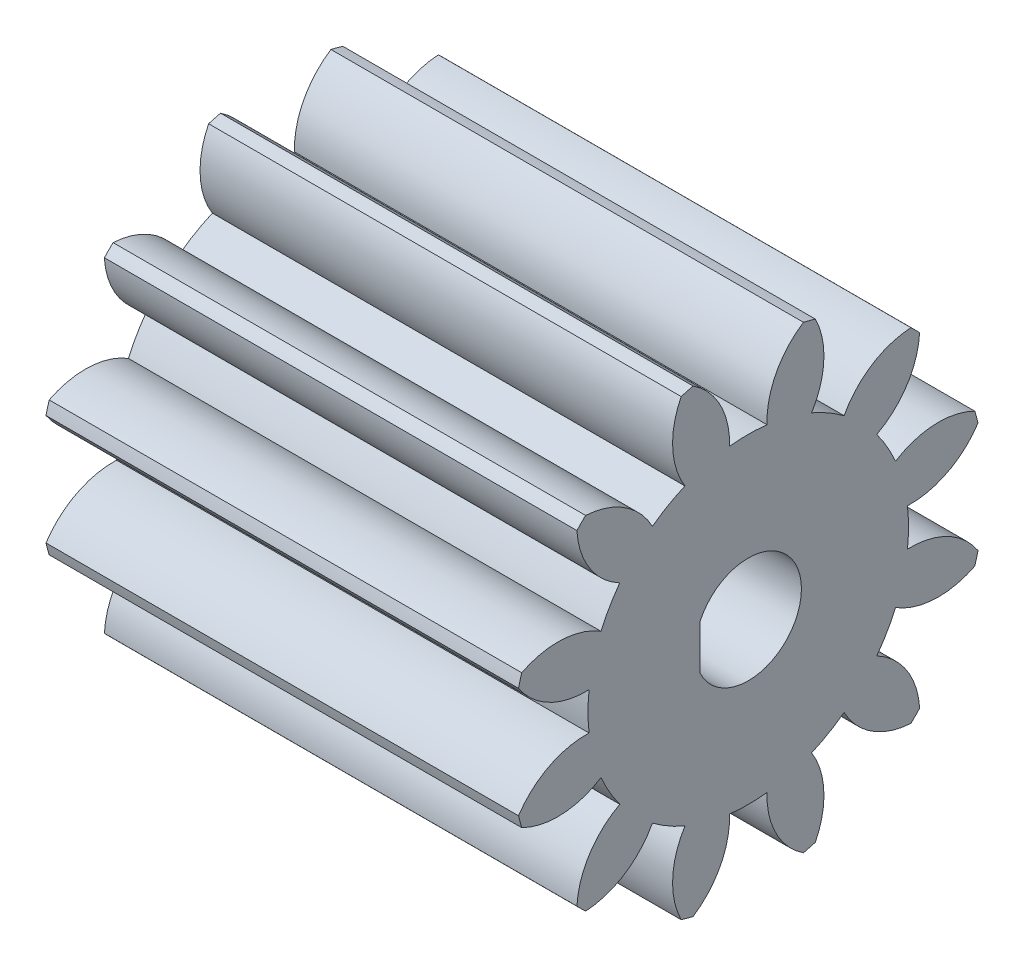
SolidWorks part; units mm, degrees
ref_plane "Plane1" through (0, 0, 0) normal (0, 0, 1) x (1, 0, 0)
ref_plane "Plane2" through (0, 0, 0) normal (0, 1, 0) x (1, 0, 0)
ref_plane "Plane3" through (0, 0, 0) normal (1, 0, 0) x (0, 0, -1)
sketch "HoldingSke" plane through (0, 0, 0) normal (0, 1, 0) x (1, 0, 0)
  line L0 (0, 0) -> (0.4891, -0.104)
  line L1 (-15, 0) -> (100, 0) construction
  line L2 (0, 0) -> (-2.1039, 2.3779)
  line L3 (0, 0) -> (-11.863, 4.5341)
  line L4 (0, 0) -> (8.4473, 1.7955)
  line L5 (0, 0) -> (-46.8476, -17.4728)
  line L6 (0, 0) -> (-23.211, -15.6605)
  line L7 (-2.1039, 2.3779) -> (8.6586, 51.2059)
  line L8 (-76.2, 54.61) -> (-74.4, 54.61)
  line L9 (-71.009, 38.7566) -> (-53.1078, 45.2721)
  line L10 (-76.2, 71.12) -> (104.1128, 71.12)
  line L11 (0, 0) -> (-28, 0)
  line L12 (-76.2, 101.6) -> (-76.133, 101.6)
  line L13 (24.9733, 27.94) -> (52.9518, 28.4284)
  line L14 (24.9733, 27.94) -> (24.9743, 27.94)
  line L15 (24.9733, 27.94) -> (100.4006, 29.5858)
  line L16 (-63.627, -2) -> (-12.827, -2)
  circle A0 centre (0, 0) radius 5
  circle A1 centre (0, 0) radius 9.499
  circle A2 centre (0, 0) radius 37.5
  circle A3 centre (0, 0) radius 5
  dimension "MHD" = 18.998
  dimension "Hub_dia" = 75
  dimension "Bore" = 10
  dimension "MBD" = 10
  dimension "Num_teeth" = 12
  dimension "Pitch" = 0.5
  dimension "Overall_len" = 50
  dimension "Show_teeth" = 12
  dimension "Thickness" = 28
  dimension "OAL" = 50.0001
  dimension "T_dim" = 1.8
  dimension "Ap" = 20
  dimension "H" = 19.05
  dimension "Pitch_radius" = 180.3128
  dimension "Width" = 28
  dimension "Backlash" = 0.067
  dimension "Addendum_fac" = 1
  dimension "Dedendum_fac" = 1.25
  dimension "Clearance_fac" = 0.25
  dimension "Dedendum_add" = 0.001
  dimension "Module" = 2
sketch "BasProSke" plane through (0, 0, 0) normal (0, 1, 0) x (1, 0, 0)
  line L0 (-10, 0) -> (60, 0) construction
  line L1 (0, 0) -> (0, 14)
  line L2 (0, 0) -> (28, 0)
  line L3 (28, 0) -> (28, 14)
  line L4 (28, 14) -> (0, 14)
  dimension "Thickness" = 28
  dimension "Diameter" = 28
revolve "Base-Revolve" add sketch "BasProSke" angle 360 about L0
sketch "TooCutSke" plane through (0, 0, 0) normal (1, 0, 0) x (0, 0, -1)
  line L1 (0, 0) -> (0, 107) construction
  line L2 (0, 0) -> (-1.6834, 11.8813) construction
  line L3 (0, 0) -> (-6.1662, 23.0126) construction
  line L4 (-1.6834, 11.8813) -> (-3.0831, 11.5063) construction
  arc A0 (1.1119, 9.4337) -> (-1.1119, 9.4337) centre (0, 0) ccw
  arc A1 (3.2981, 13.6321) -> (-3.2981, 13.6321) centre (0, 0) ccw
  circle A2 centre (0, 0) radius 12 construction
  circle A3 centre (0, 0) radius 11.2763 construction
  arc A4 (-1.1119, 9.4337) -> (-3.2981, 13.6321) centre (-5.9089, 9.6042) ccw
  arc A5 (3.2981, 13.6321) -> (1.1119, 9.4337) centre (5.9089, 9.6042) ccw
  dimension "Root_dia" = 18.998
  dimension "Overcut_dia" = 28.0508
  dimension "Pitch_dia" = 24
  dimension "Base_dia" = 22.5526
  dimension "Flank_rad" = 4.8
  dimension "Half_ang" = 15
  dimension "Half_CT" = 1.4491
extrude "ToothCut" cut sketch "TooCutSke" along normal through all
fillet "Breaks" [suppressed] radius 0.04
fillet "RootFillets" [suppressed] radius 0.501
pattern_circular "TeethCuts" count 12 every 30 about axis through (-10, 0, 0) along (1, 0, 0) of "ToothCut", "RootFillets", "Breaks"
sketch "HubNeaOneSke" plane through (0, 0, 0) normal (-1, 0, 0) x (0, 0, 1)
  circle A0 centre (0, 0) radius 9.499
  dimension "Diameter" = 18.998
extrude "HubNearOne" [suppressed] add sketch "HubNeaOneSke" along normal blind 22.0001
sketch "HubNeaBotSke" plane through (0, 0, 0) normal (-1, 0, 0) x (0, 0, 1)
  circle A0 centre (0, 0) radius 9.499
  dimension "Diameter" = 18.998
extrude "HubNearBoth" [suppressed] add sketch "HubNeaBotSke" along normal blind 11
ref_plane "FarPln" through (28, 0, 0) normal (1, 0, 0) x (0, 0, -1)
sketch "HubFarSke" plane through (28, 0, 0) normal (1, 0, 0) x (0, 0, -1)
  circle A0 centre (0, 0) radius 9.499
  dimension "Diameter" = 18.998
extrude "HubFar" [suppressed] add sketch "HubFarSke" along normal blind 11
sketch "BorSke" plane through (0, 0, 0) normal (1, 0, 0) x (0, 0, -1)
  circle A0 centre (0, 0) radius 5
  dimension "Diameter" = 10
extrude "Bore" cut sketch "BorSke" along normal mid plane 100.0001
sketch "KeySke" plane through (0, 0, 0) normal (1, 0, 0) x (0, 0, -1)
  line L0 (-2, 0) -> (-2, 6.8)
  line L1 (-2, 6.8) -> (2, 6.8)
  line L2 (2, 6.8) -> (2, 0)
  line L3 (0, 0) -> (0, 34) construction
  line L4 (-2, 0) -> (2, 0)
  dimension "Offset" = 6.8
  dimension "Width" = 4
extrude "Keyway" cut sketch "KeySke" along normal mid plane 100.0001
pattern_circular "Keyway2" [suppressed] count 2 every 90 about axis through (-10, 0, 0) along (1, 0, 0)
sketch "Esboço1" plane through (28, 0, 0) normal (1, 0, 0) x (0, 0, -1)
  circle A0 centre (0, 0) radius 9.499
extrude "Ressalto-extrusão1" add sketch "Esboço1" against normal up to surface (28 mm away) up to face at (0, 0, 0)
sketch "Esboço2" plane through (28, 0, 0) normal (1, 0, 0) x (0, 0, -1)
  line L2 (-2.85, 1.3416) -> (-2.85, -1.3416)
  arc A0 (-2.85, -1.3416) -> (-2.85, 1.3416) centre (0, 0) ccw
  point P7 (4.2126, -3.9537)
  dimension "D1" = 6.3
  dimension "D2" = 6
extrude "Corte-extrusão1" cut sketch "Esboço2" against normal up to next
equation "' \"Module@HoldingSke\" = 6.35"
equation "' \"Num_teeth@HoldingSke\" = 12"
equation "' \"Ap@HoldingSke\" =  20"
equation "' \"Ap@HoldingSke\" = 20"
equation "' \"Width@HoldingSke\" = 0.5 * 25.4"
equation "' \"Hub_dia@HoldingSke\"= 1 * 25.4"
equation "' \"Hub_dia@HoldingSke\" = 1 * 25.4"
equation "' \"Overall_len@HoldingSke\" = 1.0 * 25.4"
equation "' \"Bore@HoldingSke\" = 0.75 * 25.4"
equation "' \"T_dim@HoldingSke\" = 0.1 * 25.4"
equation "' \"Width@KeySke\" = 0.25 * 25.4"
equation "' \"Show_teeth@HoldingSke\" = 13"
equation "' \"Backlash@HoldingSke\" = 0.009 * 25.4"
equation "' \"Addendum_fac@HoldingSke\" = 1.0"
equation "' \"Dedendum_fac@HoldingSke\" = 1.25"
equation "' \"Dedendum_add@HoldingSke\" = 0.00005 * 25.4"
equation "' \"Clearance_fac@HoldingSke\" = 0.25"
equation "\"Pitch@HoldingSke\" = 1 / \"Module@HoldingSke\""
equation "\"Overcut_dia@TooCutSke\" = (\"Num_teeth@HoldingSke\" + 2 * \"Addendum_fac@HoldingSke\") / \"Pitch@HoldingSke\" + 0.002 * 25.4"
equation "\"Pitch_dia@TooCutSke\" = \"Num_teeth@HoldingSke\" / \"Pitch@HoldingSke\""
equation "\"Base_dia@TooCutSke\" = \"Num_teeth@HoldingSke\" / \"Pitch@HoldingSke\" * cos((\"Ap@HoldingSke\"  * 3.14159265 / 180))"
equation "\"Root_dia@TooCutSke\" = (\"Num_teeth@HoldingSke\" + 2) / \"Pitch@HoldingSke\" - 2 * (\"Addendum_fac@HoldingSke\" + \"Dedendum_fac@HoldingSke\") / \"Pitch@HoldingSke\" - \"Dedendum_add@HoldingSke\" * 2"
equation "\"Half_ang@TooCutSke\" = 180 / \"Num_teeth@HoldingSke\""
equation "\"Half_CT@TooCutSke\" = \"Num_teeth@HoldingSke\" / \"Pitch@HoldingSke\" * sin((3.14159265 / 2 / \"Num_teeth@HoldingSke\")) / 2 - 7 * \"Backlash@HoldingSke\" / 4"
equation "\"Flank_rad@TooCutSke\" = \"Num_teeth@HoldingSke\" / \"Pitch@HoldingSke\" / 5"
equation "\"Radius@RootFillets\" = \"Clearance_fac@HoldingSke\" / \"Pitch@HoldingSke\" + \"Dedendum_add@HoldingSke\""
equation "\"Break_rad@Breaks\" = 0.02 / \"Pitch@HoldingSke\""
equation "\"Thickness@HoldingSke\" = \"Width@HoldingSke\""
equation "\"OAL@HoldingSke\" = \"Thickness@HoldingSke\""
equation "\"MHD@HoldingSke\" = (\"Num_teeth@HoldingSke\" + 2) / \"Pitch@HoldingSke\" - 2 * (\"Addendum_fac@HoldingSke\" + \"Dedendum_fac@HoldingSke\")  / \"Pitch@HoldingSke\" - \"Dedendum_add@HoldingSke\" * 2"
equation "\"MBD@HoldingSke\" = (\"Num_teeth@HoldingSke\" + 2) / \"Pitch@HoldingSke\" - 2 * (\"Addendum_fac@HoldingSke\" + \"Dedendum_fac@HoldingSke\")  / \"Pitch@HoldingSke\" - \"Dedendum_add@HoldingSke\" * 2 - 0.002 * 25.4"
equation "\"MHD@HoldingSke\" = ((sgn( \"MHD@HoldingSke\" - \"Hub_dia@HoldingSke\" )-1)*( \"MHD@HoldingSke\" - \"Hub_dia@HoldingSke\" ))/-2+ \"Hub_dia@HoldingSke\""
equation "\"MBD@HoldingSke\" = ((sgn( \"MBD@HoldingSke\" - \"Bore@HoldingSke\" )-1)*( \"MBD@HoldingSke\" - \"Bore@HoldingSke\" ))/-2+ \"Bore@HoldingSke\""
equation "\"OAL@HoldingSke\" = ((sgn( \"OAL@HoldingSke\" - \"Overall_len@HoldingSke\" )+1)*( \"OAL@HoldingSke\" - \"Overall_len@HoldingSke\" ))/2 + \"Overall_len@HoldingSke\" + 0.000002 * 25.4"
equation "\"Num_teeth@TeethCuts\" = int( \"Show_teeth@HoldingSke\" ) + 1"
equation "\"Num_teeth@TeethCuts\" = ((sgn( \"Num_teeth@TeethCuts\" - \"Num_teeth@HoldingSke\" )-1)*( \"Num_teeth@TeethCuts\" - \"Num_teeth@HoldingSke\" ))/-2+ \"Num_teeth@HoldingSke\""
equation "\"Num_teeth@TeethCuts\" = ((sgn( \"Num_teeth@TeethCuts\" - 2.0)+1)*( \"Num_teeth@TeethCuts\" - 2.0))/2 +2.0"
equation "\"Angle@TeethCuts\" = 360.0 / \"Num_teeth@HoldingSke\""
equation "\"Diameter@BasProSke\" = (\"Num_teeth@HoldingSke\" + 2 * \"Addendum_fac@HoldingSke\") / \"Pitch@HoldingSke\""
equation "\"Thickness@BasProSke\"  = \"Thickness@HoldingSke\""
equation "' \"Fillet_rad@BasProSke\" =  \"Thickness@HoldingSke\" * 0.05"
equation "' \"Fillet_rad@BasProSke\" = \"Thickness@HoldingSke\" * 0.05"
equation "\"MHD@HoldingSke\" = ((sgn( \"MHD@HoldingSke\" - \"Root_dia@TooCutSke\" )-1)*( \"MHD@HoldingSke\" - \"Root_dia@TooCutSke\" ))/-2+ \"Root_dia@TooCutSke\""
equation "\"Diameter@HubNeaOneSke\" = \"MHD@HoldingSke\""
equation "\"Length@HubNearOne\" = \"OAL@HoldingSke\" - \"Thickness@BasProSke\""
equation "\"Diameter@HubNeaBotSke\" = \"MHD@HoldingSke\""
equation "\"Length@HubNearBoth\" = ( \"OAL@HoldingSke\" - \"Thickness@BasProSke\" ) / 2.0"
equation "\"Thickness@FarPln\" = \"Thickness@BasProSke\""
equation "\"Diameter@HubFarSke\" = \"MHD@HoldingSke\""
equation "\"Length@HubFar\" = ( \"OAL@HoldingSke\" - \"Thickness@BasProSke\" ) / 2.0"
equation "\"Diameter@BorSke\" = \"MBD@HoldingSke\""
equation "\"D1@Bore\" = \"OAL@HoldingSke\" * 2.0"
equation "\"D1@Keyway\" = \"OAL@HoldingSke\" * 2.0"
equation "\"Offset@KeySke\" = \"T_dim@HoldingSke\" + \"MBD@HoldingSke\" / 2.0"
